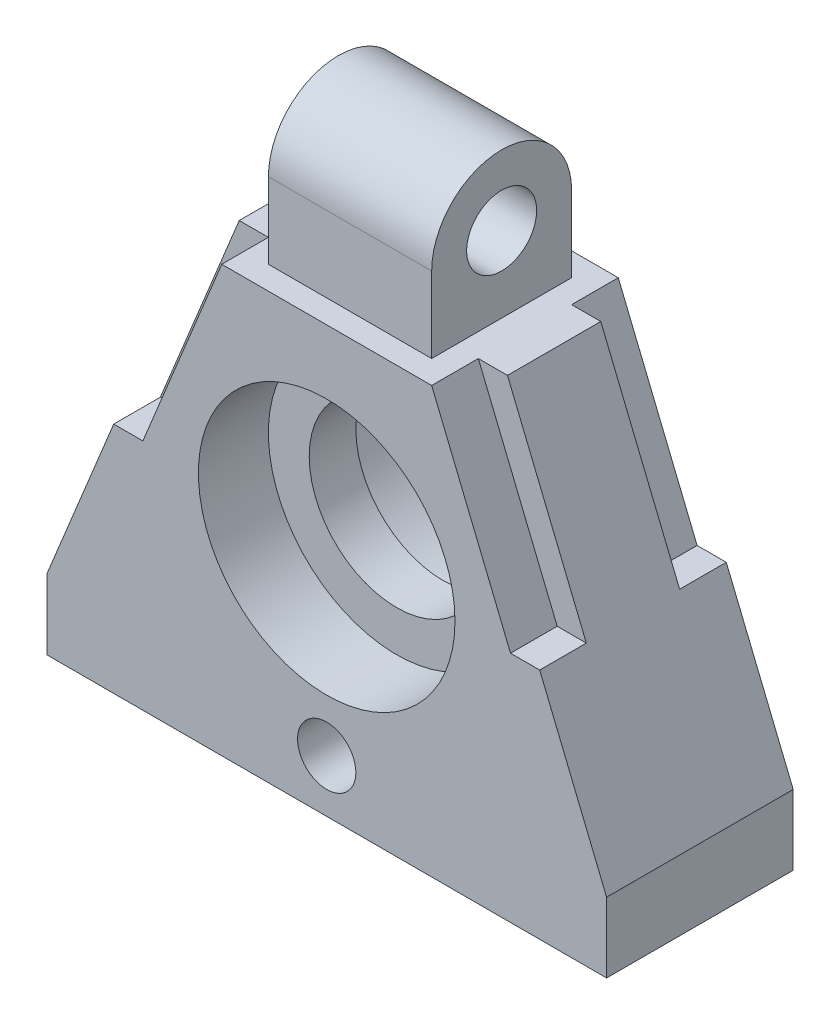
SolidWorks part; units mm, degrees
ref_plane "Alzado" through (0, 0, 0) normal (0, 0, 1) x (1, 0, 0)
ref_plane "Planta" through (0, 0, 0) normal (0, 1, 0) x (1, 0, 0)
ref_plane "Vista lateral" through (0, 0, 0) normal (1, 0, 0) x (0, 0, -1)
sketch "Croquis1" plane through (0, 0, 0) normal (0, 0, 1) x (1, 0, 0)
  line L0 (-23, 73) -> (23, 73)
  line L1 (23, 73) -> (48, 12)
  line L2 (48, 12) -> (48, 0)
  line L3 (48, 0) -> (-48, 0)
  line L4 (-48, 0) -> (-48, 12)
  line L5 (-48, 12) -> (-23, 73)
  circle A0 centre (0, 40) radius 15
  circle A1 centre (0, 9) radius 5
  point P3 (0, 73)
  point P7 (0, 0)
  dimension "D5" = 10
  dimension "D6" = 30
  dimension "D1" = 73
  dimension "D2" = 46
  dimension "D3" = 96
  dimension "D4" = 12
  dimension "D7" = 9
  dimension "D8" = 33
extrude "Saliente-Extruir1" add sketch "Croquis1" along normal mid plane 32
sketch "Croquis2" plane through (0, 0, 16) normal (0, 0, 1) x (1, 0, 0)
  circle A1 centre (0, 40) radius 22
  circle A2 centre (0, 40) radius 15
  circle A3 centre (0, 40) radius 15 construction
  dimension "D1" = 44
extrude "Cortar-Extruir1" cut sketch "Croquis2" against normal blind 12
sketch "Croquis3" plane through (0, 0, 16) normal (0, 0, 1) x (1, 0, 0)
  line L0 (0, 62) -> (0, 18) construction
  line L1 (23, 73) -> (36.5246, 40)
  line L2 (48, 12) -> (23, 73) construction
  line L3 (36.5246, 40) -> (31.5246, 40)
  line L4 (31.5246, 40) -> (18, 73)
  line L5 (23, 73) -> (-23, 73) construction
  line L6 (18, 73) -> (23, 73)
  line L7 (-18, 73) -> (-23, 73)
  line L8 (-31.5246, 40) -> (-18, 73)
  line L9 (-36.5246, 40) -> (-31.5246, 40)
  line L10 (-23, 73) -> (-36.5246, 40)
  circle A0 centre (0, 40) radius 22 construction
  circle A1 centre (0, 40) radius 22 construction
  point P16 (0, 40)
  dimension "D1" = 5
extrude "Cortar-Extruir2" cut sketch "Croquis3" against normal blind 8
mirror "Simetría1" about plane through (0, 0, 0) normal (0, 0, 1) of "Cortar-Extruir2", "Cortar-Extruir1"
sketch "Croquis4" plane through (0, 0, 0) normal (1, 0, 0) x (0, 0, -1)
  line L0 (-12, 73) -> (12, 73)
  line L1 (12, 73) -> (12, 86)
  line L2 (-12, 86) -> (-12, 73)
  line L3 (-8, 73) -> (8, 73) construction
  arc A0 (12, 86) -> (-12, 86) centre (0, 86) ccw
  circle A1 centre (0, 86) radius 6
  dimension "D1" = 12
  dimension "D2" = 12
  dimension "D3" = 86
extrude "Saliente-Extruir2" add sketch "Croquis4" along normal mid plane 28
